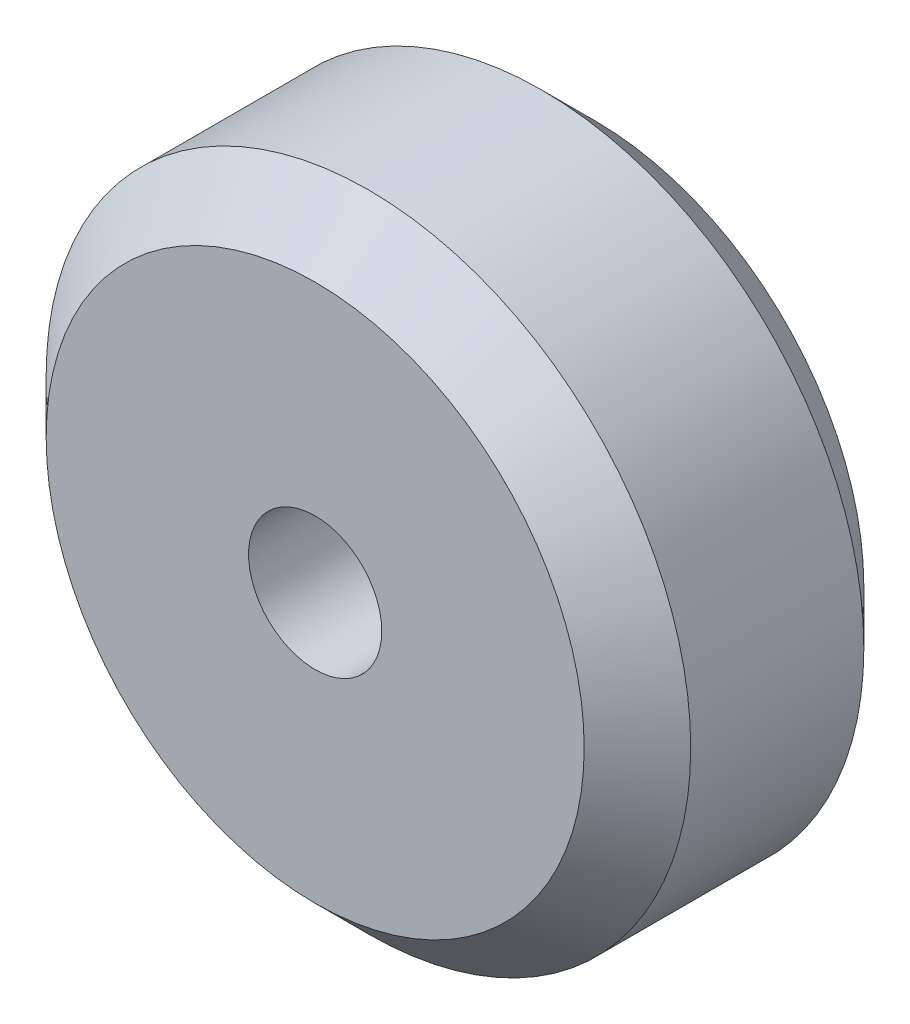
SolidWorks part; units mm, degrees
ref_plane "Front Plane" through (0, 0, 0) normal (0, 0, 1) x (1, 0, 0)
ref_plane "Top Plane" through (0, 0, 0) normal (0, 1, 0) x (1, 0, 0)
ref_plane "Right Plane" through (0, 0, 0) normal (1, 0, 0) x (0, 0, -1)
sketch "Sketch1" plane through (0, 0, 0) normal (0, 0, 1) x (1, 0, 0)
  circle A0 centre (0, 0) radius 12.1
  dimension "D1" = 24.2
extrude "Boss-Extrude1" add sketch "Sketch1" along normal blind 10.5
sketch "Sketch2" plane through (0, 0, 10.5) normal (0, 0, 1) x (1, 0, 0)
  circle A0 centre (0, 0) radius 2.5
  dimension "D1" = 5
extrude "Cut-Extrude1" cut sketch "Sketch2" against normal through all
chamfer "Chamfer1" distance 2 angle 45 2 edges at (12.1, 0, 0) (12.1, 0, 10.5)
